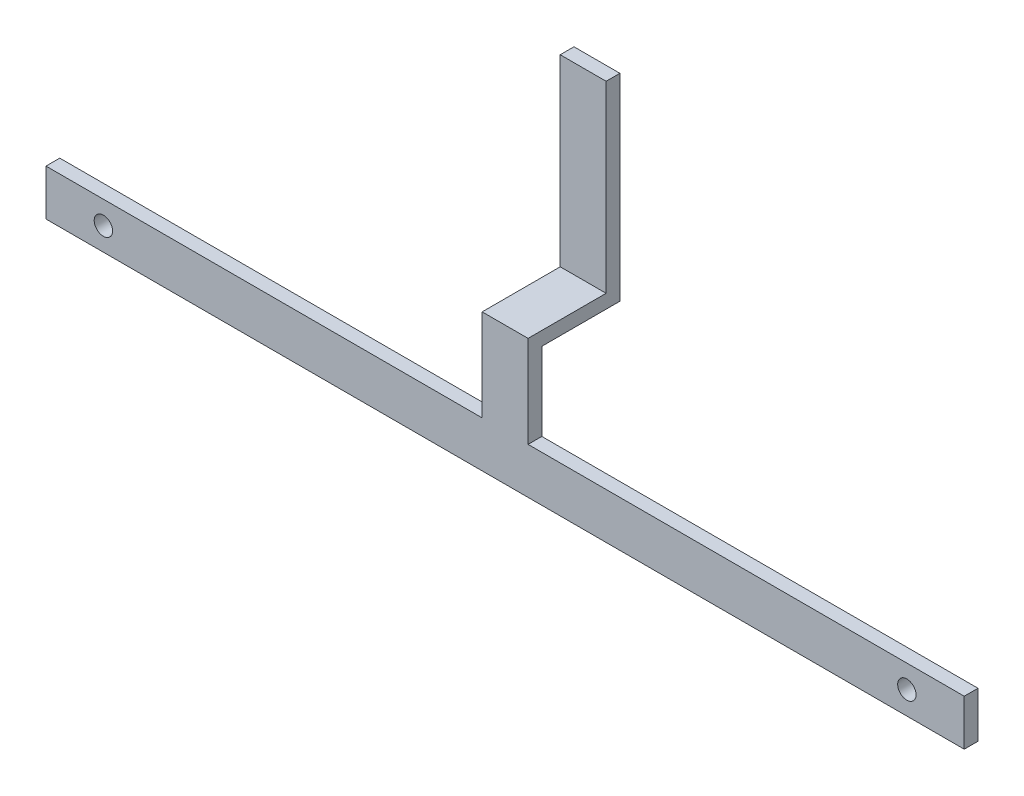
SolidWorks part; units mm, degrees
ref_plane "Front Plane" through (0, 0, 0) normal (0, 0, 1) x (1, 0, 0)
ref_plane "Top Plane" through (0, 0, 0) normal (0, 1, 0) x (1, 0, 0)
ref_plane "Right Plane" through (0, 0, 0) normal (1, 0, 0) x (0, 0, -1)
sketch "Sketch1" plane through (0, 0, 0) normal (0, 0, 1) x (1, 0, 0)
  line L1 (0, 0) -> (200, 0)
  line L2 (0, 0) -> (0, -10)
  line L3 (0, -10) -> (200, -10)
  line L4 (200, 0) -> (200, -10)
  circle A0 centre (12.5, -5) radius 2
  circle A1 centre (187.5, -5) radius 2
  point P9 (200, -5)
  dimension "D3" = 4
  dimension "D4" = 4
  dimension "D1" = 200
  dimension "D2" = 10
  dimension "D5" = 12.5
  dimension "D6" = 5
  dimension "D7" = 5
  dimension "D8" = 12.5
extrude "Boss-Extrude1" add sketch "Sketch1" along normal blind 3
sketch "Sketch2" plane through (0, 0, 3) normal (0, 0, 1) x (1, 0, 0)
  line L0 (200, 0) -> (0, 0) construction
  line L1 (95, 20) -> (105, 20)
  line L2 (95, 20) -> (95, 0)
  line L3 (95, 0) -> (105, 0)
  line L4 (105, 20) -> (105, 0)
  point P6 (100, 0)
  dimension "D1" = 10
  dimension "D2" = 20
  dimension "D3" = 5
extrude "Boss-Extrude2" add sketch "Sketch2" against normal blind 3
sketch "Sketch3" plane through (0, 0, 0) normal (0, 0, -1) x (-1, 0, 0)
  line L0 (-95, 20) -> (-95, 0) construction
  line L1 (-105, 20) -> (-95, 20)
  line L2 (-105, 20) -> (-105, 17)
  line L3 (-105, 17) -> (-95, 17)
  line L4 (-95, 20) -> (-95, 17)
  dimension "D1" = 3
extrude "Boss-Extrude3" add sketch "Sketch3" along normal blind 17
sketch "Sketch4" plane through (0, 20, 0) normal (0, 1, 0) x (1, 0, 0)
  line L0 (105, 17) -> (105, -3) construction
  line L1 (95, 17) -> (105, 17)
  line L2 (95, 17) -> (95, 14)
  line L3 (95, 14) -> (105, 14)
  line L4 (105, 17) -> (105, 14)
  dimension "D1" = 3
extrude "Boss-Extrude4" add sketch "Sketch4" along normal blind 40
equation "\"D7@Sketch1\"=\"D6@Sketch1\""
equation "\"D8@Sketch1\"=\"D5@Sketch1\""
